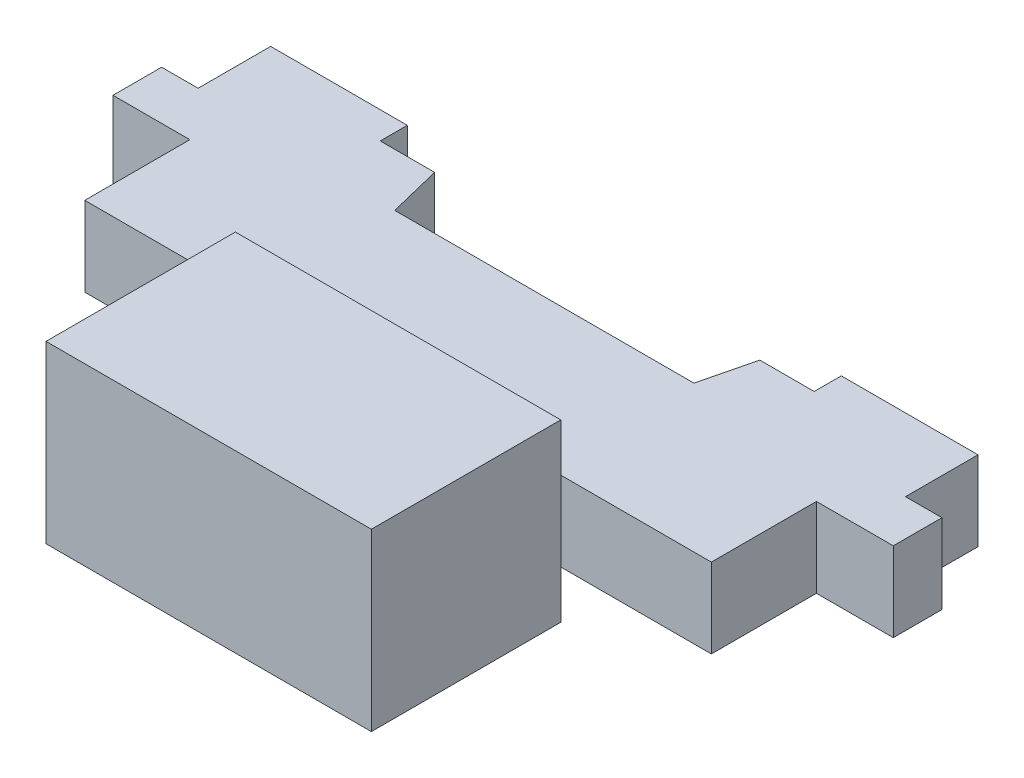
SolidWorks part; units mm, degrees
ref_plane "Front Plane" through (0, 0, 0) normal (0, 0, 1) x (1, 0, 0)
ref_plane "Top Plane" through (0, 0, 0) normal (0, 1, 0) x (1, 0, 0)
ref_plane "Right Plane" through (0, 0, 0) normal (1, 0, 0) x (0, 0, -1)
sketch "Sketch1" plane through (0, 0, 0) normal (0, 1, 0) x (1, 0, 0)
  line L0 (-18.8595, 0) -> (18.8595, 0)
  line L1 (18.8595, 0) -> (20.4978, 6.6675)
  line L2 (20.4978, 6.6675) -> (27.3558, 6.6675)
  line L3 (27.3558, 6.6675) -> (27.3558, 10.0838)
  line L4 (27.3558, 10.0838) -> (44.5897, 10.0838)
  line L5 (44.5897, 10.0838) -> (44.5897, 0.9398)
  line L6 (44.5897, 0.9398) -> (49.1871, 0.9398)
  line L7 (49.1871, 0.9398) -> (49.1871, -5.1943)
  line L8 (49.1871, -5.1943) -> (39.497, -5.1943)
  line L9 (39.497, -5.1943) -> (39.497, -18.4404)
  line L10 (39.497, -18.4404) -> (-39.497, -18.4404)
  line L11 (0, 0) -> (0, -18.4404) construction
  line L12 (-39.497, -5.1943) -> (-39.497, -18.4404)
  line L13 (-49.1871, -5.1943) -> (-39.497, -5.1943)
  line L14 (-49.1871, 0.9398) -> (-49.1871, -5.1943)
  line L15 (-44.5897, 0.9398) -> (-49.1871, 0.9398)
  line L16 (-44.5897, 10.0838) -> (-44.5897, 0.9398)
  line L17 (-27.3558, 10.0838) -> (-44.5897, 10.0838)
  line L18 (-27.3558, 6.6675) -> (-27.3558, 10.0838)
  line L19 (-20.4978, 6.6675) -> (-27.3558, 6.6675)
  line L20 (-18.8595, 0) -> (-20.4978, 6.6675)
  dimension "D1" = 18.4404
  dimension "D2" = 18.8595
  dimension "D3" = 20.4978
  dimension "D4" = 6.6675
  dimension "D5" = 6.858
  dimension "D6" = 17.2339
  dimension "D7" = 3.4163
  dimension "D8" = 6.1341
  dimension "D9" = 9.144
  dimension "D10" = 49.1871
  dimension "D11" = 39.497
extrude "Boss-Extrude1" add sketch "Sketch1" along normal mid plane 10.033
sketch "Sketch2" plane through (0, 0, 0) normal (0, 1, 0) x (1, 0, 0)
  line L0 (-39.497, -18.4404) -> (39.497, -18.4404) construction
  line L1 (-20.5105, -18.4404) -> (20.5105, -18.4404)
  line L2 (-20.5105, -18.4404) -> (-20.5105, -42.3164)
  line L3 (-20.5105, -42.3164) -> (20.5105, -42.3164)
  line L4 (20.5105, -18.4404) -> (20.5105, -42.3164)
  line L5 (-20.5105, -18.4404) -> (20.5105, -42.3164) construction
  line L6 (-20.5105, -42.3164) -> (20.5105, -18.4404) construction
  point P0 (0, -30.3784)
  dimension "D1" = 23.876
  dimension "D2" = 41.021
extrude "Boss-Extrude2" add sketch "Sketch2" along normal mid plane 22.098
